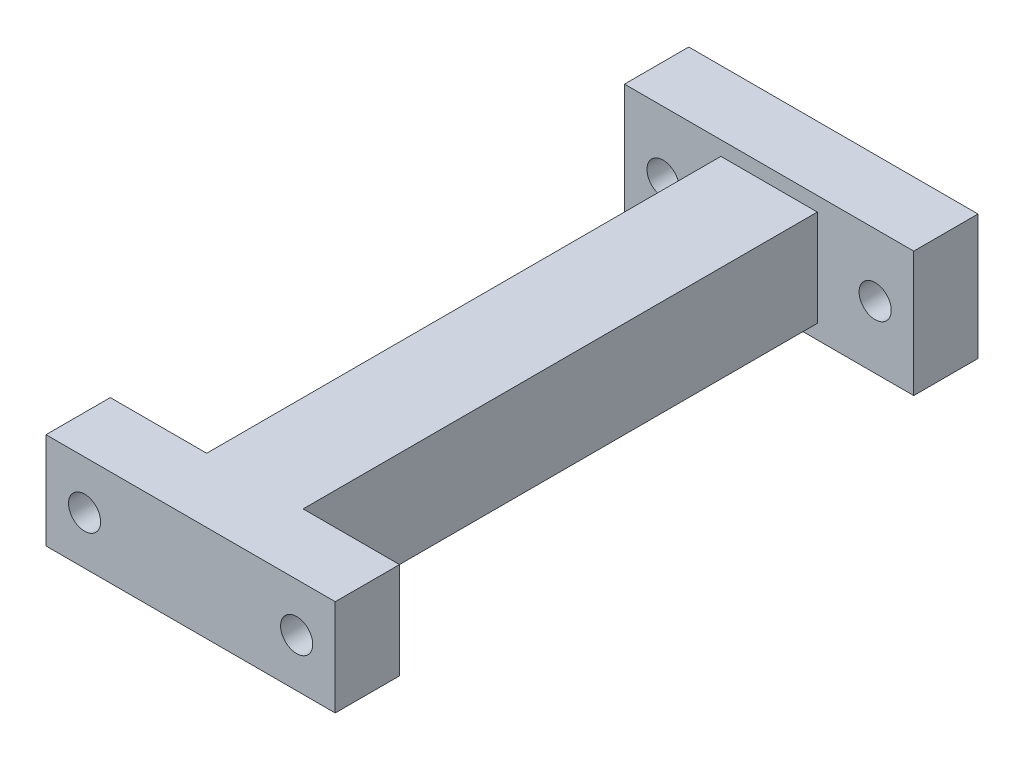
SolidWorks part; units mm, degrees
ref_plane "前视基准面" through (0, 0, 0) normal (0, 0, 1) x (1, 0, 0)
ref_plane "上视基准面" through (0, 0, 0) normal (0, 1, 0) x (1, 0, 0)
ref_plane "右视基准面" through (0, 0, 0) normal (1, 0, 0) x (0, 0, -1)
sketch "草图1" plane through (0, 0, 0) normal (0, 0, 1) x (1, 0, 0)
  line L1 (7.5, -7.5) -> (-7.5, -7.5)
  line L2 (7.5, -7.5) -> (7.5, 7.5)
  line L3 (7.5, 7.5) -> (-7.5, 7.5)
  line L4 (-7.5, -7.5) -> (-7.5, 7.5)
  line L5 (7.5, -7.5) -> (-7.5, 7.5) construction
  line L6 (7.5, 7.5) -> (-7.5, -7.5) construction
  point P0 (0, 0)
  dimension "D1" = 15
  dimension "D2" = 15
extrude "凸台-拉伸1" add sketch "草图1" along normal blind 100
sketch "草图2" plane through (0, 0, 100) normal (0, 0, 1) x (1, 0, 0)
  line L1 (22.5, -7.5) -> (-22.5, -7.5)
  line L2 (22.5, -7.5) -> (22.5, 7.5)
  line L3 (22.5, 7.5) -> (-22.5, 7.5)
  line L4 (-22.5, -7.5) -> (-22.5, 7.5)
  line L5 (22.5, -7.5) -> (-22.5, 7.5) construction
  line L6 (22.5, 7.5) -> (-22.5, -7.5) construction
  point P0 (0, 0)
  dimension "D1" = 15
  dimension "D2" = 45
extrude "凸台-拉伸2" add sketch "草图2" against normal blind 10
sketch "草图3" plane through (0, 0, 100) normal (0, 0, 1) x (1, 0, 0)
  line L0 (-22.5, 7.5) -> (-22.5, -7.5) construction
  line L2 (0, -10.71) -> (0, 10.71) construction
  circle A0 centre (-16.5, 0) radius 2.5
  circle A1 centre (16.5, 0) radius 2.5
  dimension "D1" = 6
  dimension "D2" = 5
extrude "切除-拉伸1" cut sketch "草图3" against normal blind 20
sketch "草图5" plane through (0, 0, 0) normal (0, 0, -1) x (-1, 0, 0)
  line L1 (22.5, -9.7364) -> (-22.5, -9.7364)
  line L2 (22.5, -9.7364) -> (22.5, 9.7364)
  line L3 (22.5, 9.7364) -> (-22.5, 9.7364)
  line L4 (-22.5, -9.7364) -> (-22.5, 9.7364)
  line L5 (22.5, -9.7364) -> (-22.5, 9.7364) construction
  line L6 (22.5, 9.7364) -> (-22.5, -9.7364) construction
  point P0 (0, 0)
  dimension "D1" = 45
extrude "凸台-拉伸3" add sketch "草图5" against normal blind 10
sketch "草图6" plane through (0, 0, 0) normal (0, 0, -1) x (-1, 0, 0)
  line L0 (-22.5, 9.7364) -> (-22.5, -9.7364) construction
  line L1 (22.5, -9.7364) -> (22.5, 9.7364) construction
  circle A0 centre (-16.5, 0) radius 2.5
  circle A1 centre (16.5, 0) radius 2.5
  point P6 (-22.5, 0)
  point P9 (22.5, 0)
  dimension "D1" = 6
  dimension "D3" = 5
  dimension "D4" = 5
  dimension "D2" = 6
extrude "切除-拉伸2" cut sketch "草图6" against normal through all
